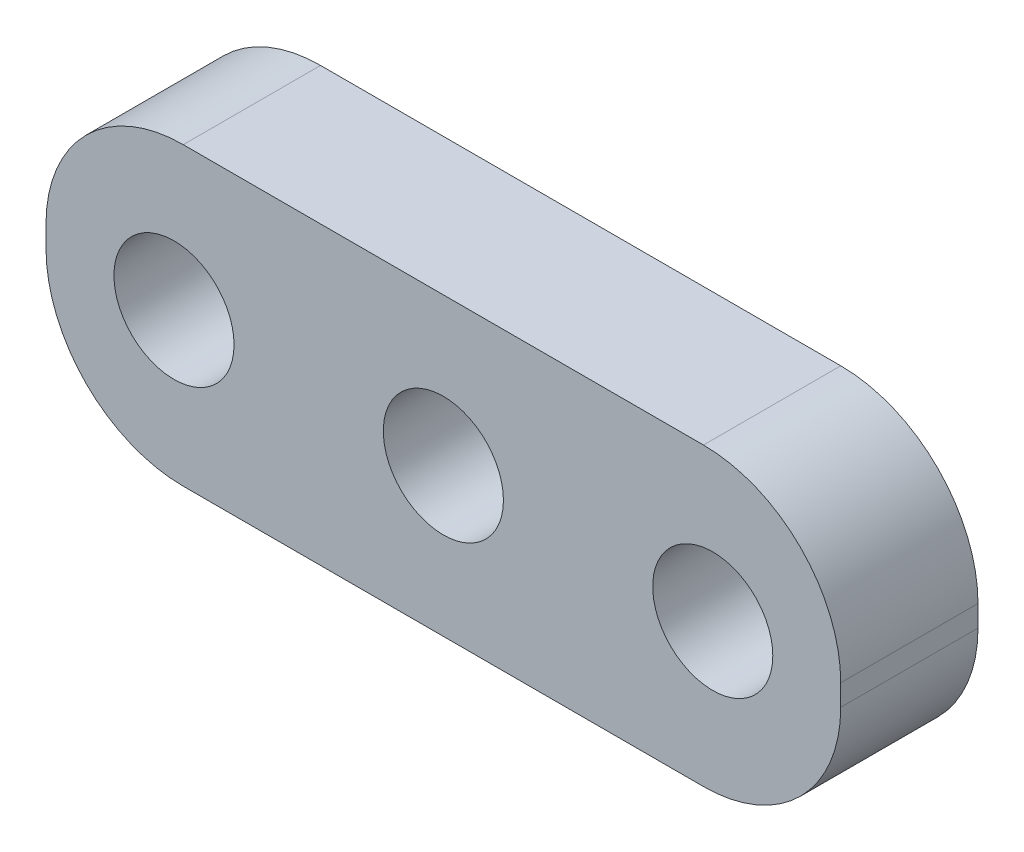
SolidWorks part; units mm, degrees
ref_plane "Front Plane" through (0, 0, 0) normal (0, 0, 1) x (1, 0, 0)
ref_plane "Top Plane" through (0, 0, 0) normal (0, 1, 0) x (1, 0, 0)
ref_plane "Right Plane" through (0, 0, 0) normal (1, 0, 0) x (0, 0, -1)
sketch "Sketch1" plane through (0, 0, 0) normal (0, 0, 1) x (1, 0, 0)
  line L0 (12.738, 0) -> (-12.738, 0) construction
  line L1 (11.58, -4.31) -> (-11.58, -4.31)
  line L2 (11.58, -4.31) -> (11.58, 4.31)
  line L3 (11.58, 4.31) -> (-11.58, 4.31)
  line L4 (-11.58, -4.31) -> (-11.58, 4.31)
  circle A0 centre (-7.85, 0) radius 1.75
  circle A1 centre (7.85, 0) radius 1.75
  circle A2 centre (0, 0) radius 1.75
  point P4 (11.58, 0)
  point P6 (0, 4.31)
  dimension "D1" = 3.73
  dimension "D3" = 15.7
  dimension "D2" = 3.73
extrude "Boss-Extrude1" add sketch "Sketch1" along normal blind 4
fillet "Fillet1" radius 4 4 edges at (11.58, -4.31, 2) (11.58, 4.31, 2) (-11.58, 4.31, 2) (-11.58, -4.31, 2)
